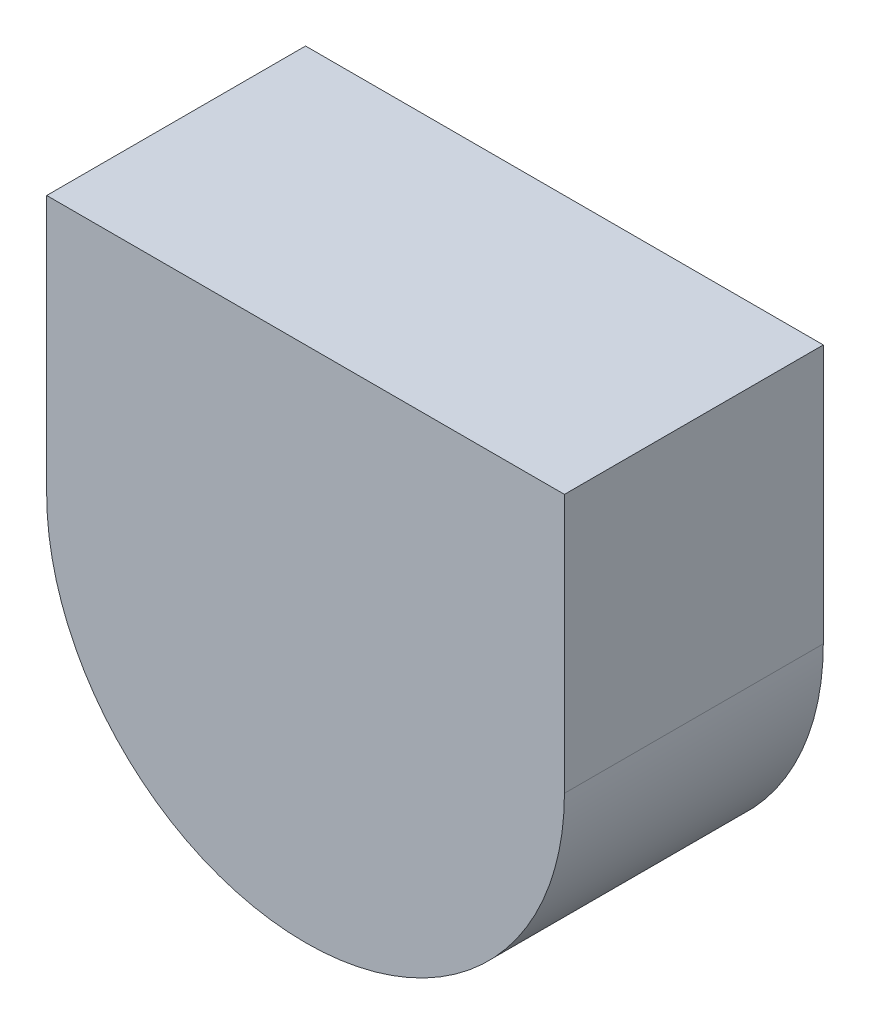
SolidWorks part; units mm, degrees
ref_plane "Front Plane" through (0, 0, 0) normal (0, 0, 1) x (1, 0, 0)
ref_plane "Top Plane" through (0, 0, 0) normal (0, 1, 0) x (1, 0, 0)
ref_plane "Right Plane" through (0, 0, 0) normal (1, 0, 0) x (0, 0, -1)
sketch "Sketch1" plane through (0, 0, 0) normal (0, 0, 1) x (1, 0, 0)
  line L0 (-2.54, 2.54) -> (-2.54, 0)
  line L1 (2.54, 2.54) -> (2.54, 0)
  line L2 (-2.54, 2.54) -> (2.54, 2.54)
  arc A0 (-2.54, 0) -> (2.54, 0) centre (0, 0) ccw
  dimension "D1" = 2.54
  dimension "D2" = 2.54
extrude "Boss-Extrude1" add sketch "Sketch1" along normal blind 2.54
